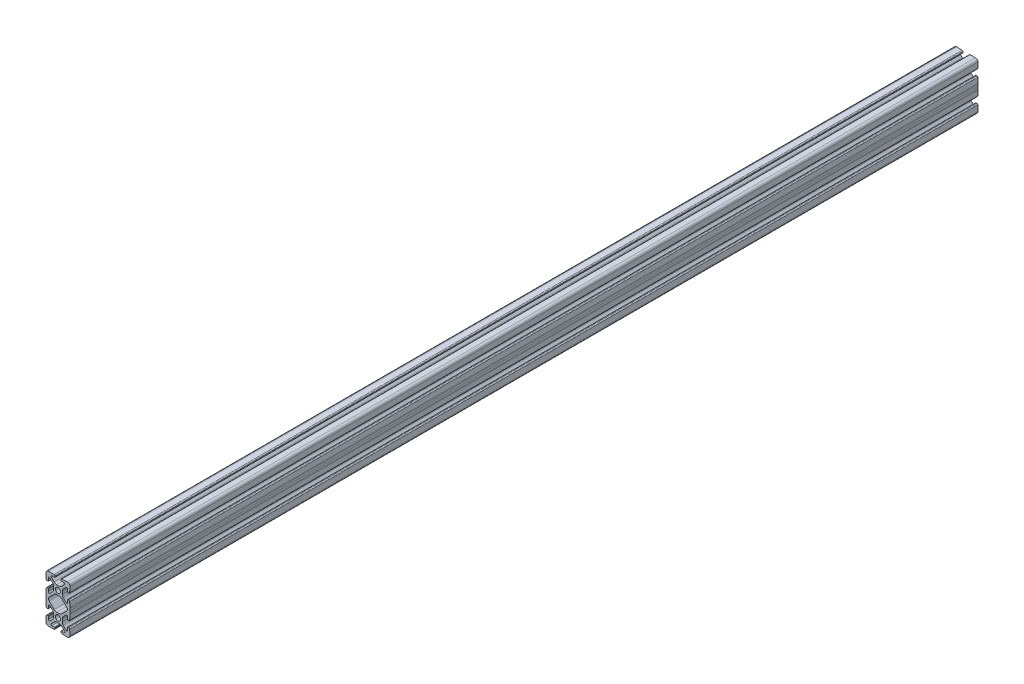
SolidWorks part; units mm, degrees
ref_plane "Front Plane" through (0, 0, 0) normal (0, 0, 1) x (1, 0, 0)
ref_plane "Top Plane" through (0, 0, 0) normal (0, 1, 0) x (1, 0, 0)
ref_plane "Right Plane" through (0, 0, 0) normal (1, 0, 0) x (0, 0, -1)
sketch "Sketch1" plane through (0, 0, 0) normal (0, 0, 1) x (1, 0, 0)
  line L0 (0, 10) -> (0, 20) construction
  line L1 (0, 10) -> (10, 10) construction
  line L2 (0, 10) -> (-10, 20) construction
  line L3 (-7.9302, 19.9988) -> (-3.2721, 19.8361)
  line L4 (-10, 20) -> (0, 20) construction
  line L6 (-2.8352, 18.0198) -> (-4.953, 18.0937)
  line L10 (0, 13.6) -> (-1.1022, 13.6)
  line L11 (-3.2236, 14.4787) -> (-5.5244, 16.7796)
  line L24 (0, 10) -> (-10, 10) construction
  line L25 (-10, 10) -> (0, 10) construction
  line L27 (-10, 0) -> (-10, 20) construction
  line L28 (0, 20) -> (10, 20) construction
  line L29 (-2.5249, 18.3091) -> (-2.5005, 19.0087)
  line L30 (-10, -20) -> (10, -20) construction
  line L31 (0, 20) -> (0, -20) construction
  arc A0 (-9.4142, 19.4142) -> (-7.9302, 19.9988) centre (-8, 18) cw
  arc A5 (-3.2721, 19.8361) -> (-2.5005, 19.0087) centre (-3.3, 19.0366) cw
  arc A6 (-1.1022, 13.6) -> (-3.2236, 14.4787) centre (-1.1022, 16.6) cw
  circle A16 centre (0, 10) radius 2.15
  arc A18 (-5.5244, 16.7796) -> (-4.953, 18.0937) centre (-4.9799, 17.3241) cw
  arc A20 (-2.8352, 18.0198) -> (-2.5249, 18.3091) centre (-2.8247, 18.3196) ccw
  point P15 (0, -20)
  point P24 (0, 0)
  point P42 (-2.3449, 13.6)
  point P80 (-10, 10)
  dimension "D11" = 2
  dimension "D15" = 3
  dimension "Center Hole Diameter" = 4.3
  dimension "D7" = 0.8
  dimension "D8" = 0.3
  dimension "D4" = 0.7701
  dimension "D1" = 45
  dimension "D2" = 2
  dimension "Rail Width" = 20
  dimension "T-Slot Depth" = 6.4
  dimension "D9" = 1.8
  dimension "D23" = 7.2
  dimension "D5" = 11.5
  dimension "T-Slot Width" = 5
  dimension "D3" = 1.775
  dimension "D6" = 9.9598
  dimension "Rail Height" = 40
sketch "Sketch2" plane through (0, 0, 0) normal (1, 0, 0) x (0, 0, -1)
  line L0 (-1524, 0) -> (1524, 0)
  line L1 (-1524, -20) -> (-1524, 20)
  line L2 (0, 10) -> (0, 20) construction
  line L3 (0, 0) -> (0, 20) construction
  line L4 (1524, -20) -> (1524, 20)
  line L5 (-10, 10) -> (10, 10) construction
  point P0 (-1491.5, 0)
  point P3 (0, 0)
  point P7 (1491.5, 0)
  point P11 (-1524, 0)
  point P14 (1524, 0)
  point P23 (0, 10)
  dimension "D1" = 32.5
  dimension "Length" = 3048
sketch "Sketch3" plane through (0, 0, 0) normal (0, 0, 1) x (1, 0, 0)
  line L0 (-2.5249, 18.3091) -> (-2.5005, 19.0087) construction
  line L1 (0, 10) -> (-10, 20) construction
  line L2 (0, 10) -> (-10, 20) construction
  line L5 (-7.9302, 19.9988) -> (-3.2721, 19.8361) construction
  line L6 (-2.8352, 18.0198) -> (-4.953, 18.0937) construction
  line L7 (-8.3091, 7.4751) -> (-9.0087, 7.4995)
  line L17 (-2.5249, 18.3091) -> (-2.5005, 19.0087)
  line L19 (-2.8352, 18.0198) -> (-4.953, 18.0937)
  line L21 (-3.6, 10) -> (0, 10) construction
  line L22 (-3.6, 8.8978) -> (-3.6, 11.1022)
  line L23 (-4.4787, 13.2236) -> (-6.7796, 15.5244)
  line L42 (-3.2236, 14.4787) -> (-5.5244, 16.7796) construction
  line L43 (0, 13.6) -> (-1.1022, 13.6) construction
  line L44 (-7.9302, 19.9988) -> (-3.2721, 19.8361)
  line L47 (-3.2236, 14.4787) -> (-5.5244, 16.7796)
  line L48 (1.1022, 13.6) -> (-1.1022, 13.6)
  line L59 (0, 13.6) -> (0, 12.15) construction
  line L60 (-9.9988, 17.9302) -> (-9.8361, 13.2721)
  line L61 (-8.0198, 12.8352) -> (-8.0937, 14.953)
  line L62 (-8.3091, 12.5249) -> (-9.0087, 12.5005)
  line L63 (-8.0198, 7.1648) -> (-8.0937, 5.047)
  line L64 (-9.9868, 2.4128) -> (-9.8361, 6.7279)
  line L65 (1.1022, 6.4) -> (-1.1022, 6.4)
  line L66 (-3.2236, 5.5213) -> (-7.3307, 1.4142)
  line L68 (-4.4787, 6.7764) -> (-6.7796, 4.4756)
  line L73 (10, 0) -> (-10, 0) construction
  line L75 (-10, 0) -> (-9.999, 1.7266)
  line L77 (10, 0) -> (9.999, 1.7266)
  line L78 (4.4787, 6.7764) -> (6.7796, 4.4756)
  line L79 (3.2236, 5.5213) -> (7.3307, 1.4142)
  line L81 (9.9868, 2.4128) -> (9.8361, 6.7279)
  line L82 (8.0198, 7.1648) -> (8.0937, 5.047)
  line L83 (8.3091, 12.5249) -> (9.0087, 12.5005)
  line L84 (8.0198, 12.8352) -> (8.0937, 14.953)
  line L85 (9.9988, 17.9302) -> (9.8361, 13.2721)
  line L87 (3.2236, 14.4787) -> (5.5244, 16.7796)
  line L88 (7.9302, 19.9988) -> (3.2721, 19.8361)
  line L89 (4.4787, 13.2236) -> (6.7796, 15.5244)
  line L90 (3.6, 8.8978) -> (3.6, 11.1022)
  line L91 (2.8352, 18.0198) -> (4.953, 18.0937)
  line L92 (2.5249, 18.3091) -> (2.5005, 19.0087)
  line L93 (8.3091, 7.4751) -> (9.0087, 7.4995)
  line L94 (-10, 0) -> (-7.9165, 0)
  line L96 (7.9165, 0) -> (10, 0)
  arc A0 (-7.9302, 19.9988) -> (-9.4142, 19.4142) centre (-8, 18) ccw construction
  arc A1 (-2.8352, 18.0198) -> (-2.5249, 18.3091) centre (-2.8247, 18.3196) ccw construction
  arc A3 (-2.8352, 18.0198) -> (-2.5249, 18.3091) centre (-2.8247, 18.3196) ccw
  arc A5 (-7.9302, 19.9988) -> (-9.9988, 17.9302) centre (-8, 18) ccw
  arc A10 (-3.2236, 5.5213) -> (-1.1022, 6.4) centre (-1.1022, 3.4) cw
  circle A13 centre (0, 10) radius 2.15 construction
  circle A14 centre (0, 10) radius 2.15
  arc A15 (-4.4787, 13.2236) -> (-3.6, 11.1022) centre (-6.6, 11.1022) cw
  arc A16 (-8.0937, 14.953) -> (-6.7796, 15.5244) centre (-7.3241, 14.9799) cw
  arc A17 (-9.0087, 12.5005) -> (-9.8361, 13.2721) centre (-9.0366, 13.3) cw
  arc A18 (-8.0198, 12.8352) -> (-8.3091, 12.5249) centre (-8.3196, 12.8247) cw
  arc A36 (-2.5005, 19.0087) -> (-3.2721, 19.8361) centre (-3.3, 19.0366) ccw construction
  arc A38 (-4.953, 18.0937) -> (-5.5244, 16.7796) centre (-4.9799, 17.3241) ccw construction
  arc A39 (-3.2236, 14.4787) -> (-1.1022, 13.6) centre (-1.1022, 16.6) ccw construction
  arc A41 (-2.5005, 19.0087) -> (-3.2721, 19.8361) centre (-3.3, 19.0366) ccw
  arc A43 (-4.953, 18.0937) -> (-5.5244, 16.7796) centre (-4.9799, 17.3241) ccw
  arc A44 (-3.2236, 14.4787) -> (-1.1022, 13.6) centre (-1.1022, 16.6) ccw
  arc A47 (-8.0198, 7.1648) -> (-8.3091, 7.4751) centre (-8.3196, 7.1753) ccw
  arc A48 (-9.0087, 7.4995) -> (-9.8361, 6.7279) centre (-9.0366, 6.7) ccw
  arc A49 (-8.0937, 5.047) -> (-6.7796, 4.4756) centre (-7.3241, 5.0201) ccw
  arc A50 (-4.4787, 6.7764) -> (-3.6, 8.8978) centre (-6.6, 8.8978) ccw
  arc A54 (-7.9165, 0) -> (-7.3307, 1.4142) centre (-5.9165, 0) cw
  arc A55 (-9.999, 1.7266) -> (-9.9868, 2.4128) centre (10.001, 1.7148) cw
  arc A56 (9.999, 1.7266) -> (9.9868, 2.4128) centre (-10.001, 1.7148) ccw
  arc A57 (7.9165, 0) -> (7.3307, 1.4142) centre (5.9165, 0) ccw
  arc A58 (4.4787, 6.7764) -> (3.6, 8.8978) centre (6.6, 8.8978) cw
  arc A59 (8.0937, 5.047) -> (6.7796, 4.4756) centre (7.3241, 5.0201) cw
  arc A60 (9.0087, 7.4995) -> (9.8361, 6.7279) centre (9.0366, 6.7) cw
  arc A61 (8.0198, 7.1648) -> (8.3091, 7.4751) centre (8.3196, 7.1753) cw
  arc A62 (3.2236, 14.4787) -> (1.1022, 13.6) centre (1.1022, 16.6) cw
  arc A63 (4.953, 18.0937) -> (5.5244, 16.7796) centre (4.9799, 17.3241) cw
  arc A64 (2.5005, 19.0087) -> (3.2721, 19.8361) centre (3.3, 19.0366) cw
  arc A65 (8.0198, 12.8352) -> (8.3091, 12.5249) centre (8.3196, 12.8247) ccw
  arc A66 (9.0087, 12.5005) -> (9.8361, 13.2721) centre (9.0366, 13.3) ccw
  arc A67 (8.0937, 14.953) -> (6.7796, 15.5244) centre (7.3241, 14.9799) ccw
  arc A68 (4.4787, 13.2236) -> (3.6, 11.1022) centre (6.6, 11.1022) ccw
  arc A70 (3.2236, 5.5213) -> (1.1022, 6.4) centre (1.1022, 3.4) ccw
  arc A71 (7.9302, 19.9988) -> (9.9988, 17.9302) centre (8, 18) cw
  arc A72 (2.8352, 18.0198) -> (2.5249, 18.3091) centre (2.8247, 18.3196) cw
  point P59 (-9.9988, 2.0698)
  point P71 (0, 0)
  point P116 (0, 6.4)
  dimension "D1" = 20
extrude "Boss-Extrude1" add sketch "Sketch3" along normal mid plane 3048
pattern_circular "CirPattern1" count 2 over 360 about axis through (0, 0, 0) along (0, 0, 1) of "Boss-Extrude1"
ref_plane "Contact Plane 1" through (0, 20, 0) normal (0, 1, 0) x (1, 0, 0)
ref_plane "Contact Plane 2" through (10, 10, 0) normal (1, 0, 0) x (0, 0, -1)
ref_plane "Contact Plane 3" through (0, -20, 0) normal (0, -1, 0) x (-1, 0, 0)
ref_plane "Contact Plane 4" through (-10, 10, 0) normal (-1, 0, 0) x (0, 0, 1)
sketch "Sketch4" plane through (3.6, 0, 0) normal (1, 0, 0) x (0, 0, -1)
  line L0 (-1524, -20) -> (1524, -20) construction
  line L1 (-1524, 20) -> (-764, 20)
  line L2 (-1524, 20) -> (-1524, -20)
  line L3 (-1524, -20) -> (-764, -20)
  line L4 (-764, 20) -> (-764, -20)
extrude "Cut-Extrude1" cut sketch "Sketch4" against normal blind 21 and the other way blind 10 flip side to cut
equation "\"D1@Sketch2\"=\"Rail Width@Sketch1\"*1.625"
equation "\"D1@Boss-Extrude1\" = \"Length@Sketch2\""
equation "\"D1@Sketch3\"=\"Rail Width@Sketch1\""
